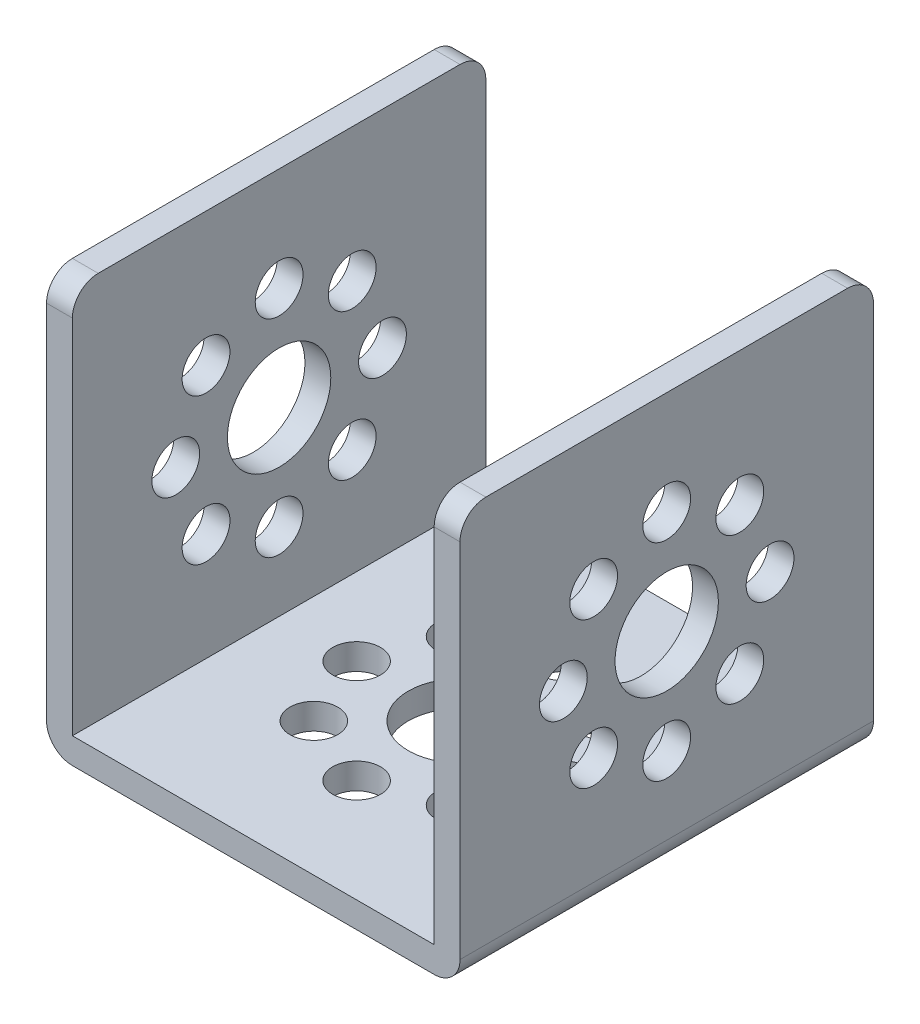
SolidWorks part; units mm, degrees
other "Defeature"
material "5052 Alloy"
ref_plane "Front Plane" through (0, 0, 0) normal (0, 0, 1) x (1, 0, 0)
ref_plane "Top Plane" through (0, 0, 0) normal (0, 1, 0) x (1, 0, 0)
ref_plane "Right Plane" through (0, 0, 0) normal (1, 0, 0) x (0, 0, -1)
sketch "Sketch3" plane through (0, 0, 0) normal (0, 0, 1) x (1, 0, 0)
  line L0 (-14, 0) -> (14, 0)
  line L1 (16, 2) -> (16, 32)
  line L2 (16, 32) -> (14, 32)
  line L3 (14, 32) -> (14, 2)
  line L4 (14, 2) -> (-14, 2)
  line L5 (-14, 2) -> (-14, 32)
  line L6 (-14, 32) -> (-16, 32)
  line L7 (-16, 32) -> (-16, 2)
  arc A0 (16, 2) -> (14, 0) centre (14, 2) cw
  arc A1 (-16, 2) -> (-14, 0) centre (-14, 2) ccw
  point P11 (16, 0)
  point P15 (0, 0)
  dimension "D7" = 2
  dimension "D1" = 2
  dimension "D2" = 2
  dimension "D3" = 32
  dimension "D4" = 32
  dimension "D5" = 32
  dimension "D6" = 30
extrude "Boss-Extrude1" add sketch "Sketch3" along normal mid plane 32
fillet "Fillet1" radius 2 2 edges at (15, 32, 16) (15, 32, -16)
fillet "Fillet2" radius 2 2 edges at (-15, 32, -16) (-15, 32, 16)
sketch "Sketch5" plane through (16, 0, 0) normal (1, 0, 0) x (0, 0, -1)
  line L0 (-14, 32) -> (14, 32) construction
  line L1 (-16, 2) -> (-16, 30) construction
  line L2 (0, 16) -> (0, 8) construction
  line L3 (-5.6569, 21.6569) -> (5.6569, 10.3431) construction
  line L4 (5.6569, 21.6569) -> (-5.6569, 10.3431) construction
  circle A0 centre (0, 16) radius 4
  circle A1 centre (0, 8) radius 1.85
  circle A2 centre (0, 24) radius 1.85
  circle A3 centre (-8, 16) radius 1.85
  circle A4 centre (8, 16) radius 1.85
  circle A5 centre (5.6569, 21.6569) radius 1.85
  circle A6 centre (-5.6569, 21.6569) radius 1.85
  circle A7 centre (5.6569, 10.3431) radius 1.85
  circle A8 centre (-5.6569, 10.3431) radius 1.85
  circle A12 centre (0, 16) radius 8 construction
  point P2 (0, 32)
  dimension "D1" = 8
  dimension "D12" = 3.7
  dimension "D4" = 16
  dimension "D2" = 16
  dimension "D3" = 16
  dimension "D5" = 45
extrude "Cut-Extrude1" cut sketch "Sketch5" against normal blind 32
sketch "Sketch8" plane through (0, 2, 0) normal (0, 1, 0) x (1, 0, 0)
  line L0 (0, 0) -> (0, -8) construction
  line L1 (-5.6569, 5.6569) -> (5.6569, -5.6569) construction
  line L2 (5.6569, 5.6569) -> (-5.6569, -5.6569) construction
  line L3 (-14, -16) -> (14, -16) construction
  line L4 (14, -16) -> (14, 16) construction
  circle A9 centre (0, 0) radius 4
  circle A10 centre (0, -8) radius 1.85
  circle A11 centre (0, 8) radius 1.85
  circle A12 centre (-8, 0) radius 1.85
  circle A13 centre (8, 0) radius 1.85
  circle A14 centre (5.6569, 5.6569) radius 1.85
  circle A15 centre (-5.6569, 5.6569) radius 1.85
  circle A16 centre (5.6569, -5.6569) radius 1.85
  circle A17 centre (-5.6569, -5.6569) radius 1.85
  circle A18 centre (0, 0) radius 8 construction
  point P2 (0, -16)
  point P6 (14, 0)
  dimension "D24" = 8
  dimension "D25" = 3.7
  dimension "D26" = 16
  dimension "D27" = 45
extrude "Cut-Extrude2" cut sketch "Sketch8" against normal blind 2
